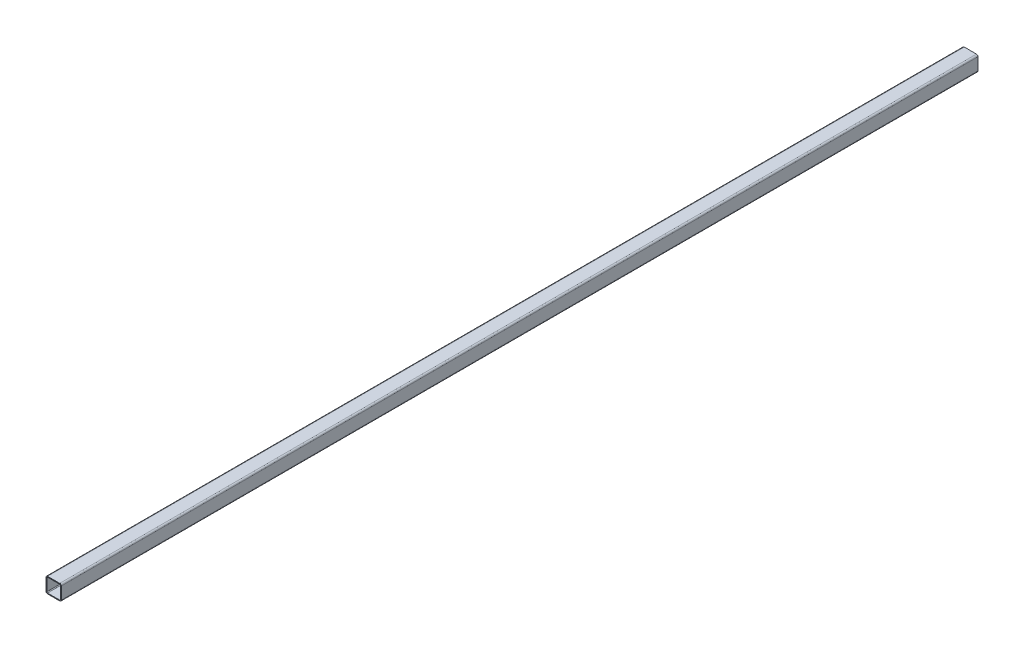
SolidWorks part; units mm, degrees
material "S355 verification"
ref_plane "Front Plane" through (0, 0, 0) normal (0, 0, 1) x (1, 0, 0)
ref_plane "Top Plane" through (0, 0, 0) normal (0, 1, 0) x (1, 0, 0)
ref_plane "Right Plane" through (0, 0, 0) normal (1, 0, 0) x (0, 0, -1)
sketch "Sketch1" plane through (0, 0, 0) normal (0, 1, 0) x (1, 0, 0)
  line L0 (0, 0) -> (0, -6000)
other "SHS100x100x5 (1)"
ref_plane "Plane1" through (0, 0, 0) normal (0, 0, 1) x (1, 0, 0)
sketch "Sketch11" plane through (0, 0, 0) normal (0, 0, 1) x (1, 0, 0)
  line L0 (-40, -50) -> (40, -50)
  line L1 (50, -40) -> (50, 40)
  line L2 (40, 50) -> (-40, 50)
  line L3 (-50, 40) -> (-50, -40)
  line L4 (-40, -45) -> (40, -45)
  line L5 (45, -40) -> (45, 40)
  line L6 (40, 45) -> (-40, 45)
  line L7 (-45, 40) -> (-45, -40)
  arc A0 (40, -50) -> (50, -40) centre (40, -40) ccw
  arc A1 (50, 40) -> (40, 50) centre (40, 40) ccw
  arc A2 (-40, 50) -> (-50, 40) centre (-40, 40) ccw
  arc A3 (-50, -40) -> (-40, -50) centre (-40, -40) ccw
  arc A4 (40, -45) -> (45, -40) centre (40, -40) ccw
  arc A5 (45, 40) -> (40, 45) centre (40, 40) ccw
  arc A6 (-40, 45) -> (-45, 40) centre (-40, 40) ccw
  arc A7 (-45, -40) -> (-40, -45) centre (-40, -40) ccw
  point P20 (0, 0)
